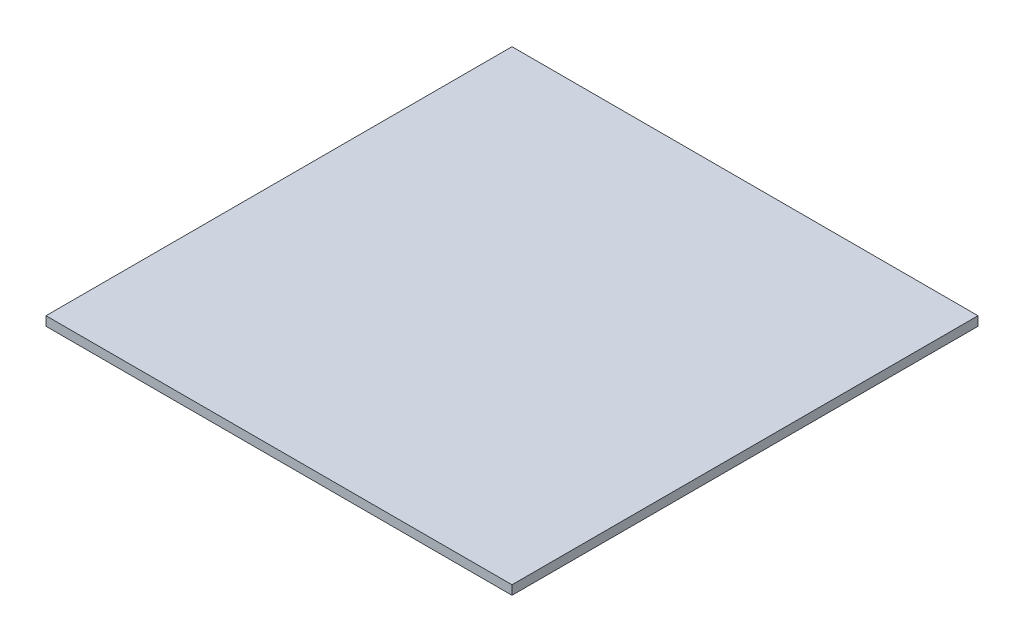
SolidWorks part; units mm, degrees
ref_plane "Front Plane" through (0, 0, 0) normal (0, 0, 1) x (1, 0, 0)
ref_plane "Top Plane" through (0, 0, 0) normal (0, 1, 0) x (1, 0, 0)
ref_plane "Right Plane" through (0, 0, 0) normal (1, 0, 0) x (0, 0, -1)
sketch "Sketch1" plane through (0, 0, 0) normal (0, 1, 0) x (1, 0, 0)
  line L1 (-152.4, -152.4) -> (152.4, -152.4)
  line L2 (-152.4, -152.4) -> (-152.4, 152.4)
  line L3 (-152.4, 152.4) -> (152.4, 152.4)
  line L4 (152.4, -152.4) -> (152.4, 152.4)
  line L5 (-152.4, -152.4) -> (152.4, 152.4) construction
  line L6 (-152.4, 152.4) -> (152.4, -152.4) construction
  point P0 (0, 0)
extrude "Boss-Extrude1" add sketch "Sketch1" along normal blind 5.9944
